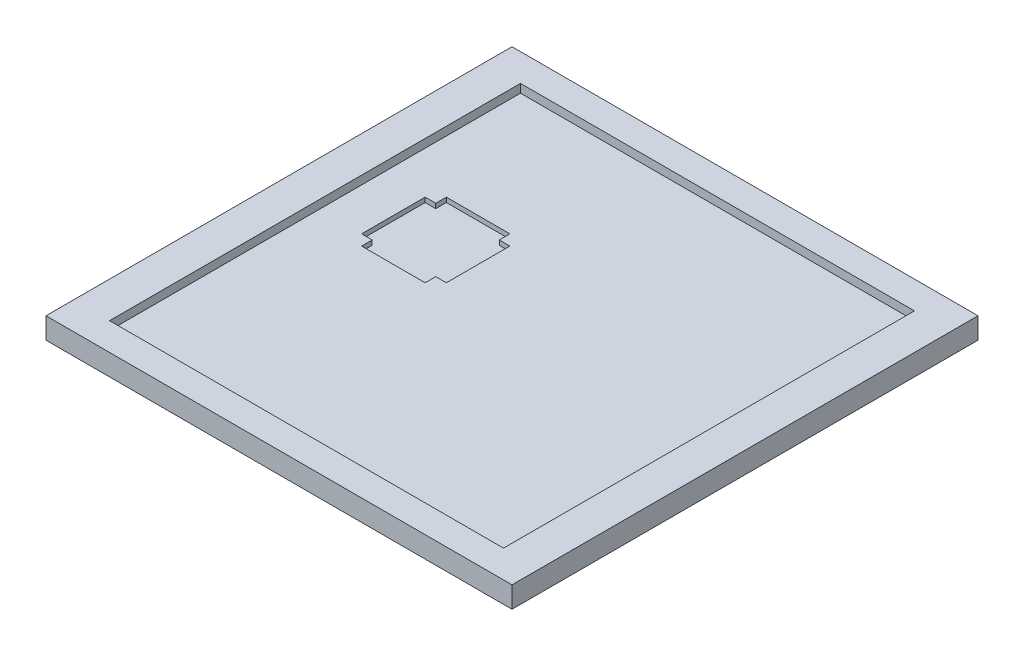
SolidWorks part; units mm, degrees
ref_plane "Front Plane" through (0, 0, 0) normal (0, 0, 1) x (1, 0, 0)
ref_plane "Top Plane" through (0, 0, 0) normal (0, 1, 0) x (1, 0, 0)
ref_plane "Right Plane" through (0, 0, 0) normal (1, 0, 0) x (0, 0, -1)
sketch "Sketch1" plane through (0, 0, 0) normal (0, 1, 0) x (1, 0, 0)
  line L1 (-68.863, 38.3493) -> (41.137, 38.3493)
  line L2 (-68.863, 38.3493) -> (-68.863, -71.6507)
  line L3 (-68.863, -71.6507) -> (41.137, -71.6507)
  line L4 (41.137, 38.3493) -> (41.137, -71.6507)
  dimension "D1" = 110
  dimension "D2" = 110
extrude "Boss-Extrude1" add sketch "Sketch1" along normal blind 5
sketch "Sketch2" plane through (0, 5, 0) normal (0, 1, 0) x (1, 0, 0)
  line L0 (41.137, 38.3493) -> (-68.863, 38.3493) construction
  line L1 (-60.363, 31.8493) -> (32.637, 31.8493)
  line L2 (-60.363, 31.8493) -> (-60.363, -65.1507)
  line L3 (-60.363, -65.1507) -> (32.637, -65.1507)
  line L4 (32.637, 31.8493) -> (32.637, -65.1507)
  line L5 (41.137, -71.6507) -> (41.137, 38.3493) construction
  point P4 (-13.863, 31.8493)
  point P7 (-13.863, 38.3493)
  point P8 (32.637, -16.6507)
  point P11 (41.137, -16.6507)
  dimension "D1" = 97
  dimension "D2" = 93
extrude "Cut-Extrude1" cut sketch "Sketch2" against normal blind 2
sketch "Sketch3" plane through (0, 3, 0) normal (0, 1, 0) x (1, 0, 0)
  line L0 (-40.363, 11.8493) -> (-40.363, -28.1507) construction
  line L1 (-60.363, 31.8493) -> (-60.363, -65.1507) construction
  line L2 (32.637, 31.8493) -> (-60.363, 31.8493) construction
  line L3 (-30.363, -0.6507) -> (-32.863, -0.6507)
  line L4 (-30.363, -0.6507) -> (-30.363, -15.6507)
  line L5 (-30.363, -15.6507) -> (-32.863, -15.6507)
  line L6 (-50.363, -0.6507) -> (-50.363, -15.6507)
  line L7 (-50.363, -0.6507) -> (-30.363, -15.6507) construction
  line L8 (-32.863, 1.8493) -> (-47.863, -18.1507) construction
  line L9 (-47.863, 1.8493) -> (-32.863, 1.8493)
  line L10 (-47.863, 1.8493) -> (-47.863, -0.6507)
  line L11 (-47.863, -18.1507) -> (-32.863, -18.1507)
  line L12 (-32.863, 1.8493) -> (-32.863, -0.6507)
  line L13 (-47.863, -0.6507) -> (-50.363, -0.6507)
  line L14 (-32.863, -15.6507) -> (-32.863, -18.1507)
  line L16 (-47.863, -15.6507) -> (-50.363, -15.6507)
  line L17 (-47.863, -15.6507) -> (-47.863, -18.1507)
  point P10 (-40.363, -8.1507)
  point P11 (-40.363, -8.1507)
  point P16 (-40.363, -8.1507)
  dimension "D1" = 20
  dimension "D2" = 20
  dimension "D3" = 15
  dimension "D4" = 20
  dimension "D5" = 40
  dimension "D6" = 15
  dimension "D7" = 20
extrude "Cut-Extrude2" cut sketch "Sketch3" against normal blind 1.1
